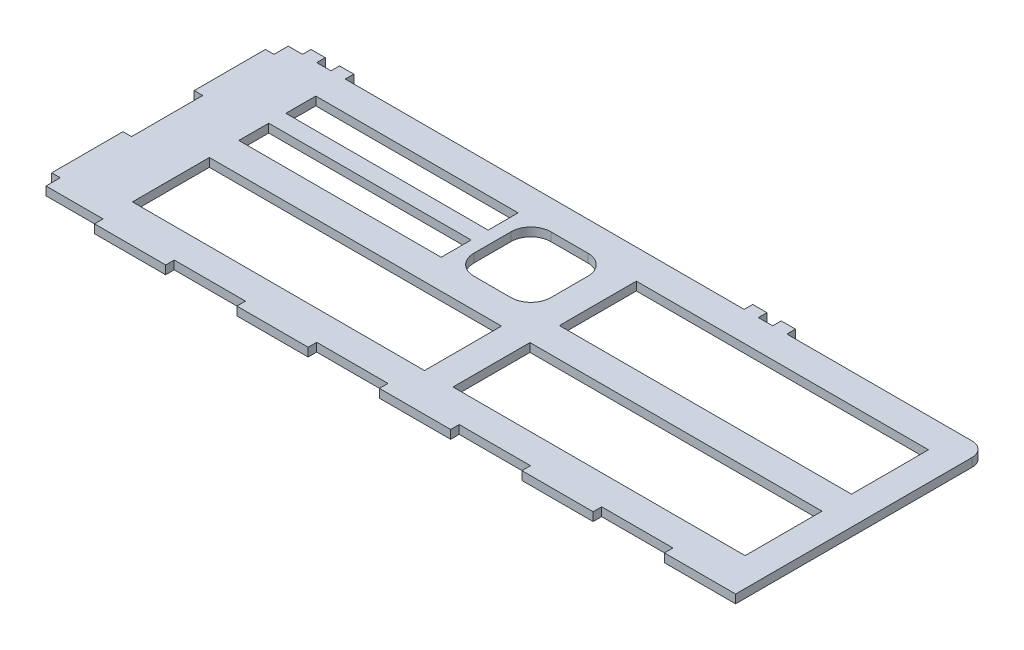
SolidWorks part; units mm, degrees
material "Buk"
ref_plane "Přední rovina" through (0, 0, 0) normal (0, 0, 1) x (1, 0, 0)
ref_plane "Horní rovina" through (0, 0, 0) normal (0, 1, 0) x (1, 0, 0)
ref_plane "Pravá rovina" through (0, 0, 0) normal (1, 0, 0) x (0, 0, -1)
sketch "Skica1" plane through (0, 0, 0) normal (0, 1, 0) x (1, 0, 0)
  line L0 (0, 0) -> (245, 0)
  line L1 (245, 0) -> (245, 85)
  line L2 (20, 37.3333) -> (122.5, 37.3333)
  line L3 (91, 74.6667) -> (91, 64.1667)
  line L4 (91, 64.1667) -> (20, 64.1667)
  line L5 (20, 64.1667) -> (20, 74.6667)
  line L6 (20, 74.6667) -> (91, 74.6667)
  line L7 (122.5, 37.3333) -> (122.5, 10.3333)
  line L8 (122.5, 10.3333) -> (20, 10.3333)
  line L9 (20, 10.3333) -> (20, 37.3333)
  line L10 (0, 85) -> (245, 85)
  line L11 (0, 85) -> (0, 0)
  line L12 (235, 74.6667) -> (235, 85) construction
  line L13 (132.5, 37.3333) -> (235, 37.3333)
  line L14 (132.5, 37.3333) -> (132.5, 10.3333)
  line L15 (132.5, 10.3333) -> (235, 10.3333)
  line L16 (235, 47.6667) -> (132.5, 47.6667)
  line L17 (235, 47.6667) -> (235, 74.6667)
  line L18 (235, 74.6667) -> (132.5, 74.6667)
  line L19 (132.5, 47.6667) -> (132.5, 74.6667)
  line L20 (235, 37.3333) -> (235, 10.3333)
  line L21 (102.5, 74.6667) -> (115.5, 74.6667)
  line L22 (95.5, 67.6667) -> (95.5, 54.6667)
  line L23 (102.5, 47.6667) -> (115.5, 47.6667)
  line L24 (122.5, 67.6667) -> (122.5, 54.6667)
  line L25 (91, 64.1667) -> (91, 58.1667) construction
  line L26 (20, 58.1667) -> (91, 58.1667)
  line L27 (235, 47.6667) -> (235, 37.3333) construction
  line L28 (235, 37.3333) -> (234.5483, 37.5149) construction
  line L29 (20, 58.1667) -> (20, 47.6667)
  line L30 (20, 47.6667) -> (91, 47.6667)
  line L31 (91, 58.1667) -> (91, 47.6667)
  line L32 (235, 10.3333) -> (235, 0) construction
  arc A0 (115.5, 47.6667) -> (122.5, 54.6667) centre (115.5, 54.6667) ccw
  arc A1 (95.5, 54.6667) -> (102.5, 47.6667) centre (102.5, 54.6667) ccw
  arc A2 (115.5, 74.6667) -> (122.5, 67.6667) centre (115.5, 67.6667) cw
  arc A3 (102.5, 74.6667) -> (95.5, 67.6667) centre (102.5, 67.6667) ccw
  dimension "D11" = 7
  dimension "D1" = 102.5
  dimension "D3" = 20
  dimension "D4" = 245
  dimension "D5" = 10
  dimension "D6" = 27
  dimension "D7" = 71
  dimension "D9" = 85
  dimension "D10" = 10.5
extrude "Přidat vysunutím1" add sketch "Skica1" along normal blind 3
sketch "Skica2" plane through (0, 0, 0) normal (0, 1, 0) x (1, 0, 0)
  line L0 (0, 30) -> (-3, 30)
  line L1 (0, 80) -> (-3, 80)
  line L2 (0, 80) -> (0, 55)
  line L3 (0, 55) -> (-3, 55)
  line L4 (-3, 80) -> (-3, 55)
  line L5 (0, 30) -> (0, 5)
  line L6 (0, 5) -> (-3, 5)
  line L7 (-3, 30) -> (-3, 5)
  line L8 (-3, 55) -> (-3, 30) construction
  line L9 (0, 0) -> (245, 0) construction
  line L10 (245, 0) -> (245, 85) construction
  line L11 (220, 0) -> (245, 0)
  line L12 (220, 0) -> (220, -3)
  line L13 (220, -3) -> (245, -3)
  line L14 (245, 0) -> (245, -3)
  line L15 (170, 0) -> (195, 0)
  line L16 (170, 0) -> (170, -3)
  line L17 (170, -3) -> (195, -3)
  line L18 (195, 0) -> (195, -3)
  line L19 (120, 0) -> (145, 0)
  line L20 (120, 0) -> (120, -3)
  line L21 (120, -3) -> (145, -3)
  line L22 (145, 0) -> (145, -3)
  line L23 (70, 0) -> (95, 0)
  line L24 (70, 0) -> (70, -3)
  line L25 (70, -3) -> (95, -3)
  line L26 (95, 0) -> (95, -3)
  line L27 (20, 0) -> (45, 0)
  line L28 (20, 0) -> (20, -3)
  line L29 (20, -3) -> (45, -3)
  line L30 (45, 0) -> (45, -3)
  line L31 (195, -3) -> (220, -3) construction
  line L37 (0, 85) -> (0, 0) construction
  line L140 (245, 85) -> (0, 85) construction
  dimension "D1" = 3
  dimension "D2" = 25
  dimension "D3" = 2
  dimension "D9" = 5
  dimension "D4" = 5
extrude "Přidat vysunutím2" add sketch "Skica2" along normal up to surface (3 mm away) up to face at (109, 3, -61.1667)
sketch "Skica3" plane through (0, 0, 0) normal (0, 1, 0) x (1, 0, 0)
  line L0 (245, 85) -> (0, 85) construction
  line L1 (5, 85) -> (10, 85)
  line L2 (5, 85) -> (5, 88)
  line L3 (5, 88) -> (10, 88)
  line L4 (10, 85) -> (10, 88)
  line L5 (0, 55) -> (0, 30) construction
  line L6 (15, 85) -> (20, 85)
  line L7 (15, 85) -> (15, 88)
  line L8 (15, 88) -> (20, 88)
  line L9 (20, 85) -> (20, 88)
  dimension "D1" = 3
  dimension "D2" = 5
  dimension "D3" = 5
  dimension "D4" = 5
extrude "Přidat vysunutím3" add sketch "Skica3" along normal up to surface (3 mm away) up to face at (109, 3, -61.1667)
sketch "Skica4" [suppressed] plane through (0, 0, 0) normal (0, 1, 0) x (1, 0, 0)
  line L0 (245, 85) -> (20, 85) construction
  line L1 (25, 85) -> (30, 85)
  line L2 (25, 85) -> (25, 88)
  line L3 (25, 88) -> (30, 88)
  line L4 (30, 85) -> (30, 88)
  line L5 (10, 88) -> (5, 88) construction
  line L6 (35, 85) -> (40, 85)
  line L7 (35, 85) -> (35, 88)
  line L8 (35, 88) -> (40, 88)
  line L9 (40, 85) -> (40, 88)
  line L10 (30, 88) -> (35, 88) construction
  line L11 (20, 88) -> (25, 88) construction
extrude "Přidat vysunutím4" [suppressed] add sketch "Skica4" along normal up to surface (3 mm away)
fillet "Zaoblit1" radius 5 1 edges at (245, 1.5, -85)
sketch "Skica6" [suppressed] plane through (0, 0, 0) normal (0, 1, 0) x (1, 0, 0)
  line L0 (5, 85) -> (0, 85) construction
  line L1 (158, 85) -> (163, 85)
  line L2 (158, 85) -> (158, 88)
  line L3 (158, 88) -> (163, 88)
  line L4 (163, 85) -> (163, 88)
  line L6 (168, 88) -> (173, 88)
  line L7 (168, 88) -> (168, 85)
  line L8 (168, 85) -> (173, 85)
  line L9 (173, 88) -> (173, 85)
  line L11 (0, 85) -> (0, 80) construction
  line L12 (10, 88) -> (5, 88) construction
  line L13 (163, 88) -> (168, 88) construction
  dimension "D2" = 158
extrude "Přidat vysunutím5" [suppressed] add sketch "Skica6" along normal up to surface (3 mm away)
sketch "Skica7" plane through (0, 0, 0) normal (0, 1, 0) x (1, 0, 0)
  line L0 (240, 85) -> (20, 85) construction
  line L1 (160, 85) -> (165, 85)
  line L2 (160, 85) -> (160, 88)
  line L3 (160, 88) -> (165, 88)
  line L4 (165, 85) -> (165, 88)
  line L5 (10, 88) -> (5, 88) construction
  line L6 (170, 85) -> (175, 85)
  line L7 (170, 85) -> (170, 88)
  line L8 (170, 88) -> (175, 88)
  line L9 (175, 85) -> (175, 88)
  line L10 (0, 85) -> (0, 80) construction
  dimension "D1" = 5
  dimension "D2" = 160
extrude "Přidat vysunutím6" add sketch "Skica7" along normal up to surface (3 mm away) up to face at (109, 3, -61.1667)
sketch "Skica8" [suppressed] plane through (0, 0, 0) normal (0, 1, 0) x (1, 0, 0)
  line L0 (0, 85) -> (0, 80) construction
  line L1 (245, 85) -> (285, 85)
  line L2 (245, 85) -> (245, 70)
  line L3 (245, 70) -> (285, 70)
  line L4 (285, 85) -> (285, 70)
  dimension "D1" = 285
  dimension "D2" = 15
extrude "Přidat vysunutím7" [suppressed] add sketch "Skica8" along normal up to surface (3 mm away)
sketch "Skica9" [suppressed] plane through (0, 0, 0) normal (0, 1, 0) x (1, 0, 0)
  line L0 (285, 70) -> (285, 85) construction
  line L1 (285, 85) -> (288, 85)
  line L2 (285, 85) -> (285, 80)
  line L3 (285, 80) -> (288, 80)
  line L4 (288, 85) -> (288, 80)
  line L5 (285, 75) -> (288, 75)
  line L6 (285, 75) -> (285, 70)
  line L7 (285, 70) -> (288, 70)
  line L8 (288, 75) -> (288, 70)
  line L10 (-3, 55) -> (0, 55) construction
  line L11 (10, 88) -> (5, 88) construction
  line L14 (288, 80) -> (288, 75) construction
extrude "Přidat vysunutím8" [suppressed] add sketch "Skica9" along normal up to surface (3 mm away)
